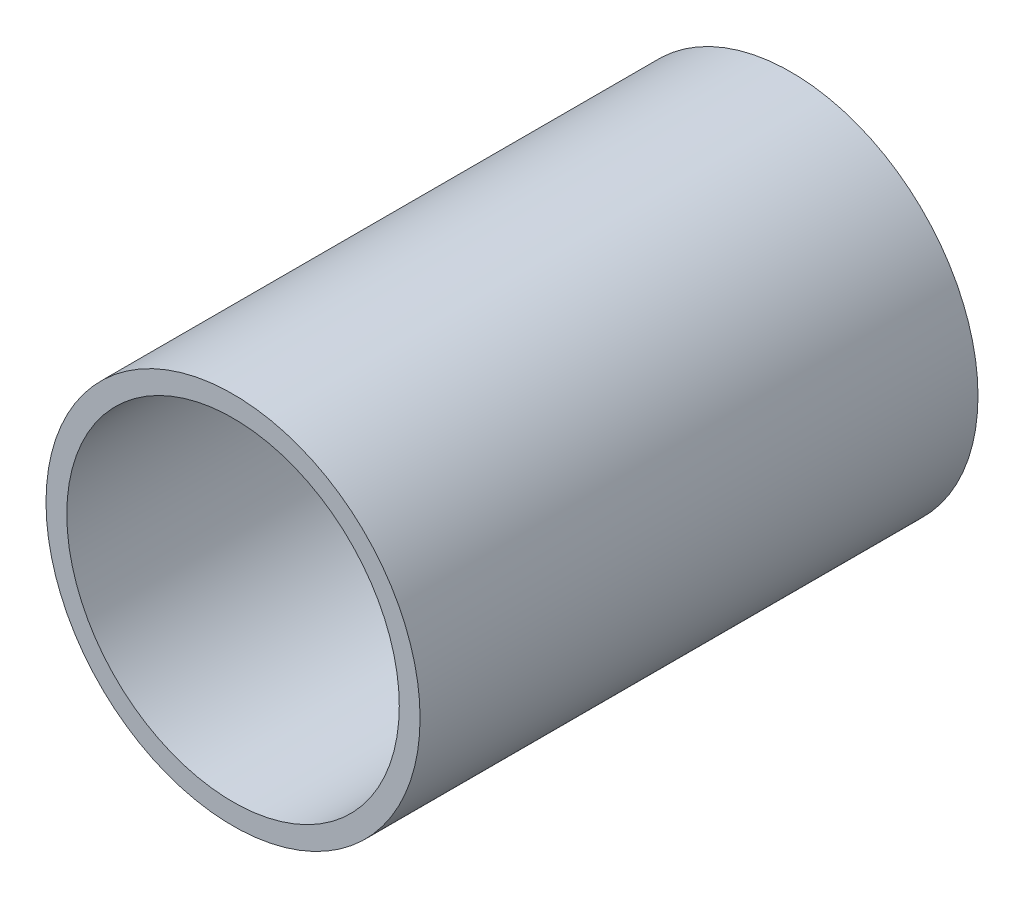
SolidWorks part; units mm, degrees
material "Acrylic (Medium-high impact)"
ref_plane "Front Plane" through (0, 0, 0) normal (0, 0, 1) x (1, 0, 0)
ref_plane "Top Plane" through (0, 0, 0) normal (0, 1, 0) x (1, 0, 0)
ref_plane "Right Plane" through (0, 0, 0) normal (1, 0, 0) x (0, 0, -1)
sketch "Sketch1" plane through (0, 0, 0) normal (0, 0, 1) x (1, 0, 0)
  line L0 (28.575, 0) -> (25.4, 0) construction
  line L1 (-28.575, 0) -> (28.575, 0) construction
  dimension "OD" = 57.15
  dimension "Wall Thickness" = 3.175
sketch "Sketch2" plane through (0, 0, 0) normal (1, 0, 0) x (0, 0, -1)
  line L0 (152.4, 0) -> (-152.4, 0)
  point P4 (0, 0)
  dimension "Length" = 304.8
sketch "Sketch3" plane through (0, 0, 0) normal (0, 0, 1) x (1, 0, 0)
  circle A0 centre (0, 0) radius 28.575
  circle A1 centre (0, 0) radius 25.4
extrude "Boss-Extrude1" add sketch "Sketch3" along normal up to vertex (152.4 mm away) and the other way up to vertex (152.4 mm away) up to point (0, 0, 152.4) other way up to point (0, 0, -152.4)
sketch "Sketch4" plane through (0, 0, 152.4) normal (0, 0, 1) x (1, 0, 0)
  circle A1 centre (0, 0) radius 28.575
  circle A2 centre (0, 0) radius 28.575
  dimension "D1" = 0
extrude "Cut-Extrude1" cut sketch "Sketch4" against normal offset from surface (219.56 mm away) 85.24 up to face at (25.4, 0, -152.4)
